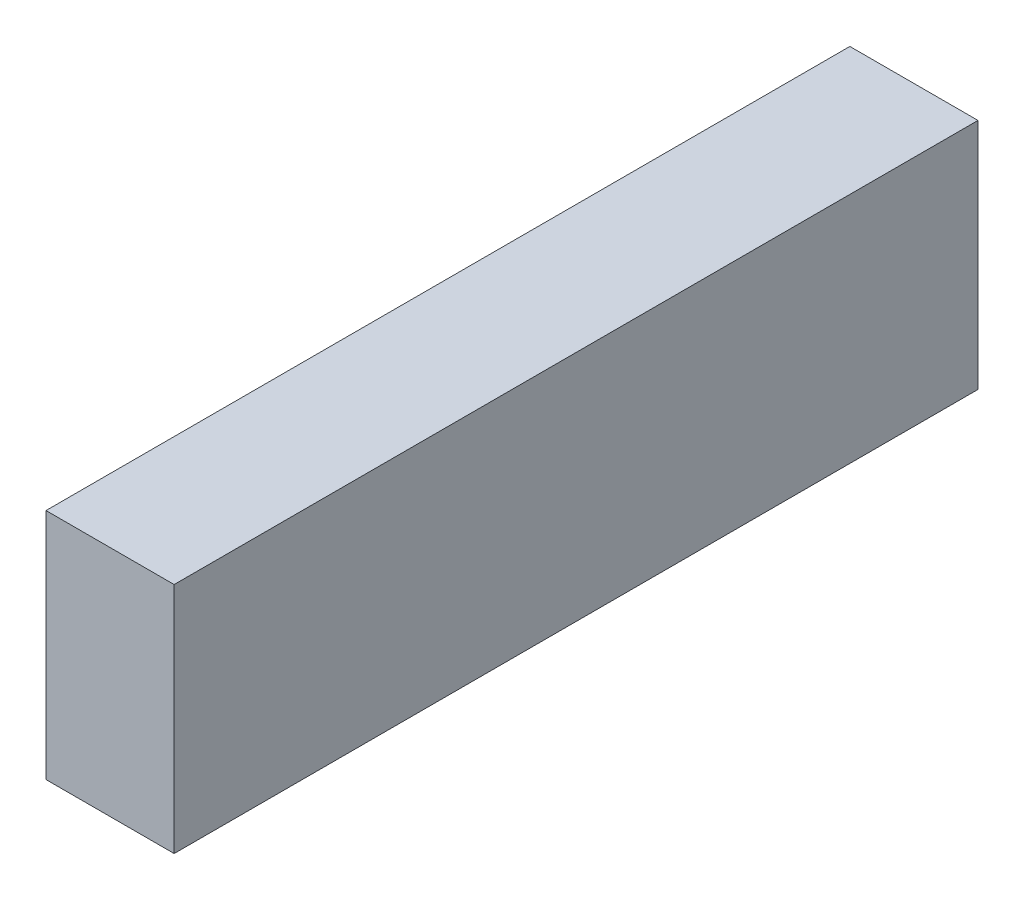
SolidWorks part; units mm, degrees
ref_plane "前视基准面" through (0, 0, 0) normal (0, 0, 1) x (1, 0, 0)
ref_plane "上视基准面" through (0, 0, 0) normal (0, 1, 0) x (1, 0, 0)
ref_plane "右视基准面" through (0, 0, 0) normal (1, 0, 0) x (0, 0, -1)
sketch "草图1" plane through (0, 0, 0) normal (0, 0, 1) x (1, 0, 0)
  line L1 (-11, 20) -> (11, 20)
  line L2 (-11, 20) -> (-11, -20)
  line L3 (-11, -20) -> (11, -20)
  line L4 (11, 20) -> (11, -20)
  line L5 (-11, 20) -> (11, -20) construction
  line L6 (-11, -20) -> (11, 20) construction
  point P0 (0, 0)
  dimension "D1" = 22
  dimension "D2" = 40
extrude "凸台-拉伸1" add sketch "草图1" along normal blind 138
